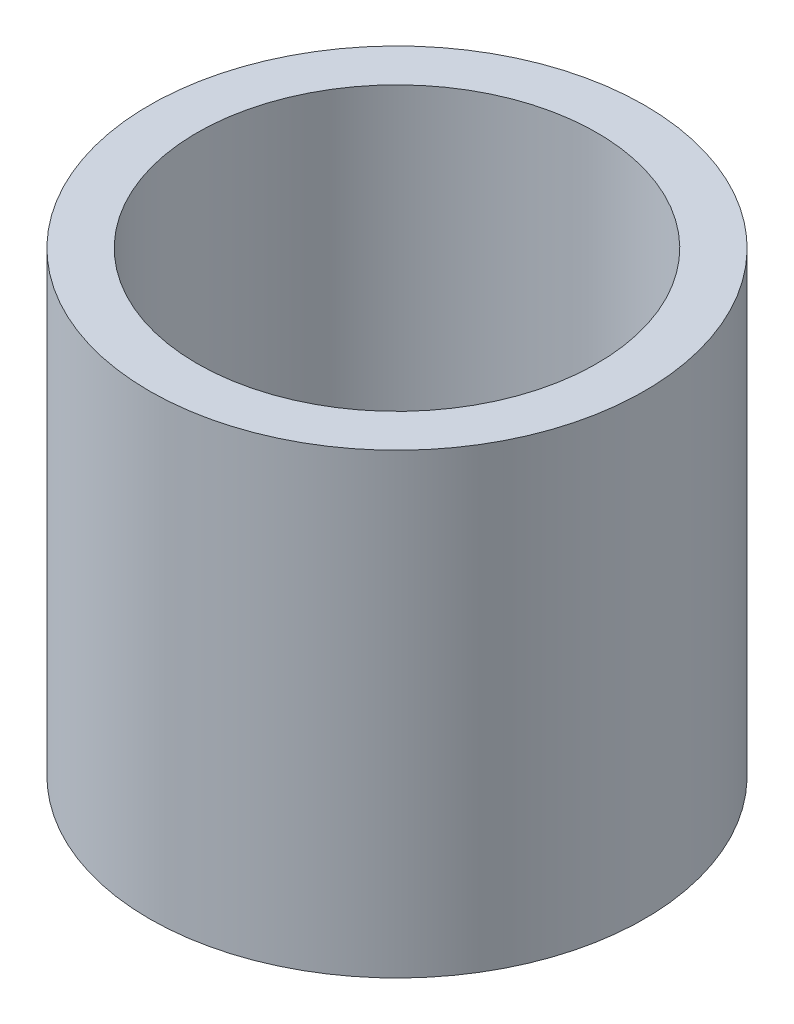
SolidWorks part; units mm, degrees
material "Polyurethane Foam Rigid"
ref_plane "Front Plane" through (0, 0, 0) normal (0, 0, 1) x (1, 0, 0)
ref_plane "Top Plane" through (0, 0, 0) normal (0, 1, 0) x (1, 0, 0)
ref_plane "Right Plane" through (0, 0, 0) normal (1, 0, 0) x (0, 0, -1)
sketch "Sketch1" plane through (0, 0, 0) normal (0, 1, 0) x (1, 0, 0)
  circle A1 centre (0, 0) radius 130
  dimension "D1" = 260
extrude "Boss-Extrude1" add sketch "Sketch1" along normal blind 240 contours A1
sketch "Sketch2" plane through (0, 240, 0) normal (0, 1, 0) x (1, 0, 0)
  circle A0 centre (0, 0) radius 105
  dimension "D1" = 210
extrude "Cut-Extrude1" cut sketch "Sketch2" against normal blind 170
sketch "Sketch3" plane through (0, 0, 0) normal (0, -1, 0) x (1, 0, 0)
  circle A0 centre (-90, 0) radius 12.5
  circle A1 centre (90, 0) radius 12.5
  circle A2 centre (0, 0) radius 32.5
  dimension "D1" = 25
  dimension "D2" = 25
  dimension "D5" = 65
  dimension "D3" = 90
  dimension "D4" = 90
extrude "Cut-Extrude2" cut sketch "Sketch3" against normal through all both and the other way through all
